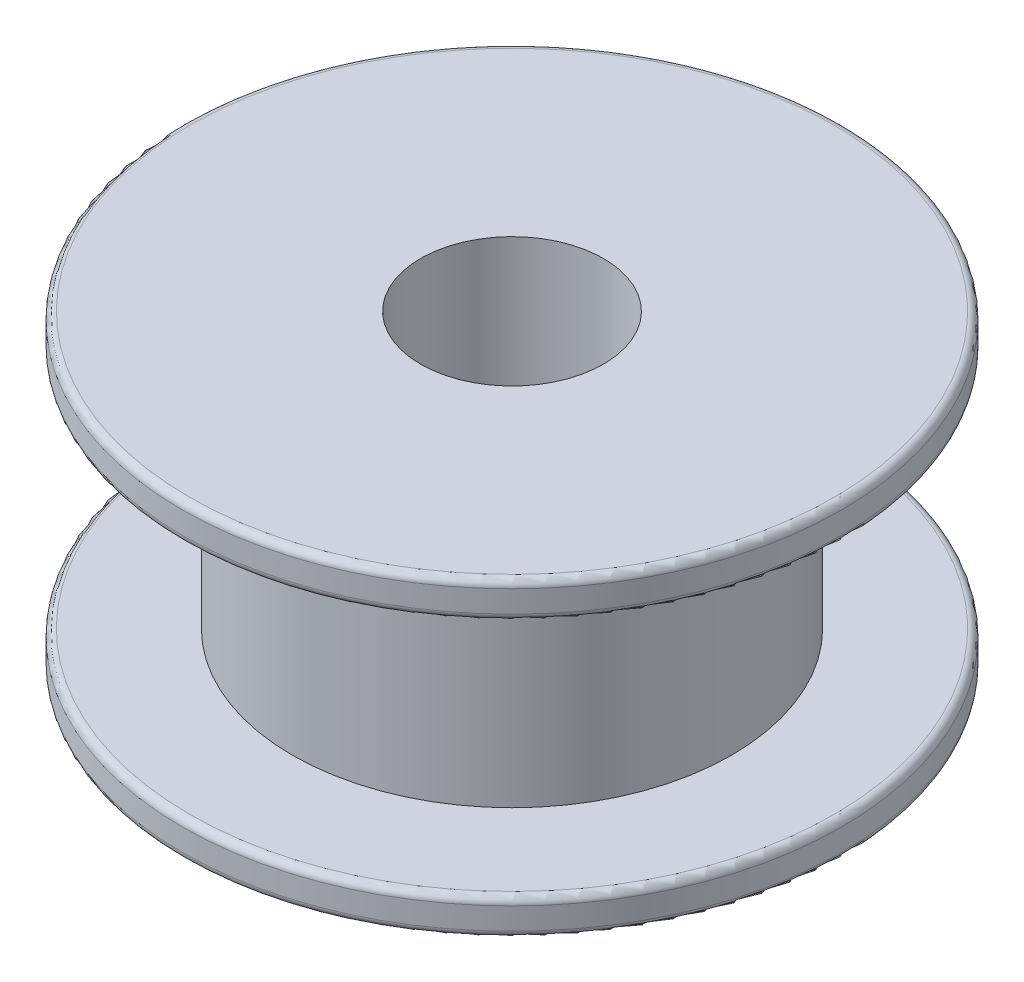
SolidWorks part; units mm, degrees
ref_plane "Front" through (0, 0, 0) normal (0, 0, 1) x (1, 0, 0)
ref_plane "Top" through (0, 0, 0) normal (0, 1, 0) x (1, 0, 0)
ref_plane "Right" through (0, 0, 0) normal (1, 0, 0) x (0, 0, -1)
sketch "Sketch1" plane through (0, 0, 0) normal (0, 1, 0) x (1, 0, 0)
  circle A0 centre (0, 0) radius 9
  dimension "D1" = 18
extrude "Boss-Extrude1" add sketch "Sketch1" along normal blind 1
sketch "Sketch2" plane through (0, 1, 0) normal (0, 1, 0) x (1, 0, 0)
  circle A0 centre (0, 0) radius 6
  dimension "D1" = 12
extrude "Boss-Extrude2" add sketch "Sketch2" along normal blind 6.5
sketch "Sketch3" plane through (0, 7.5, 0) normal (0, 1, 0) x (1, 0, 0)
  circle A1 centre (0, 0) radius 9
  circle A2 centre (0, 0) radius 9
  dimension "D1" = 0
extrude "Boss-Extrude3" add sketch "Sketch3" along normal blind 1
sketch "Sketch4" plane through (0, 8.5, 0) normal (0, 1, 0) x (1, 0, 0)
  circle A0 centre (0, 0) radius 2.5
  dimension "D1" = 5
extrude "Cut-Extrude1" cut sketch "Sketch4" against normal through all
fillet "Fillet1" radius 0.2 4 edges at (0, 1, 9) (0, 0, 9) (0, 7.5, 9) (0, 8.5, 9)
